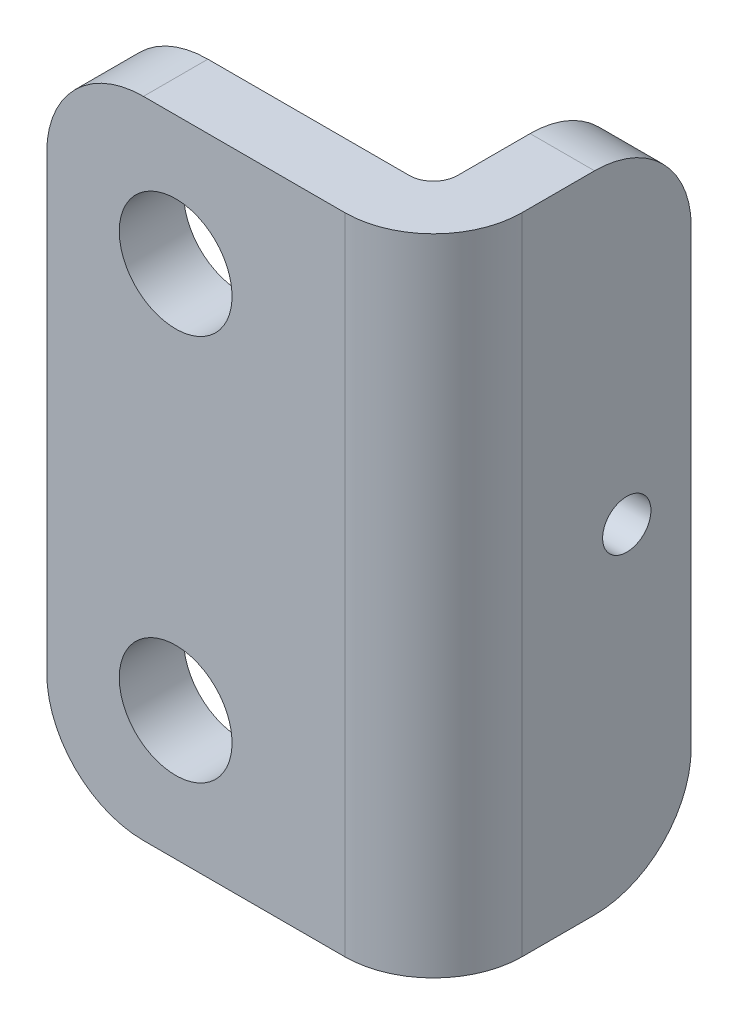
SolidWorks part; units mm, degrees
ref_plane "Front Plane" through (0, 0, 0) normal (0, 0, 1) x (1, 0, 0)
ref_plane "Top Plane" through (0, 0, 0) normal (0, 1, 0) x (1, 0, 0)
ref_plane "Right Plane" through (0, 0, 0) normal (1, 0, 0) x (0, 0, -1)
sketch "Sketch2" plane through (0, 0, 0) normal (0, 1, 0) x (1, 0, 0)
  line L0 (0, 9.46) -> (0, -7.6979) construction
  line L1 (-10.1513, 0) -> (9.9189, 0) construction
  line L2 (-1, 7) -> (1, 7)
  line L3 (1, 7) -> (1, 1.75)
  line L4 (-1.75, -1) -> (-11, -1)
  line L5 (-11, -1) -> (-11, 1)
  line L6 (-11, 1) -> (-1.75, 1)
  line L7 (-1, 1.75) -> (-1, 7)
  arc A0 (-1.75, 1) -> (-1, 1.75) centre (-1.75, 1.75) ccw
  arc A1 (1, 1.75) -> (-1.75, -1) centre (-1.75, 1.75) cw
  dimension "D5" = 0.75
  dimension "D6" = 2.75
  dimension "D1" = 2
  dimension "D2" = 1
  dimension "D3" = 2
  dimension "D4" = 1
  dimension "D7" = 12
  dimension "D8" = 8
extrude "Boss-Extrude1" add sketch "Sketch2" along normal blind 20
fillet "Fillet1" radius 3 4 edges at (0, 0, -7) (0, 20, -7) (-11, 20, 0) (-11, 0, 0)
sketch "Sketch3" plane through (0, 0, -1) normal (0, 0, -1) x (-1, 0, 0)
  line L0 (11, 10) -> (-11.7333, 10) construction
  line L1 (11, 17) -> (11, 3) construction
  line L2 (7, 0) -> (7, 4) construction
  line L3 (1.75, 0) -> (8, 0) construction
  line L4 (7, 4) -> (11, 4) construction
  circle A0 centre (7, 16) radius 1.75
  circle A1 centre (7, 4) radius 1.75
  dimension "D1" = 3.5
  dimension "D3" = 6
  dimension "D2" = 12
extrude "Cut-Extrude1" cut sketch "Sketch3" against normal through all
sketch "Sketch4" plane through (-1, 0, 0) normal (-1, 0, 0) x (0, 0, 1)
  line L0 (-7, 17) -> (-7, 3) construction
  circle A0 centre (-5, 10) radius 0.75
  dimension "D1" = 1.5
  dimension "D2" = 2
extrude "Cut-Extrude2" cut sketch "Sketch4" against normal through all
